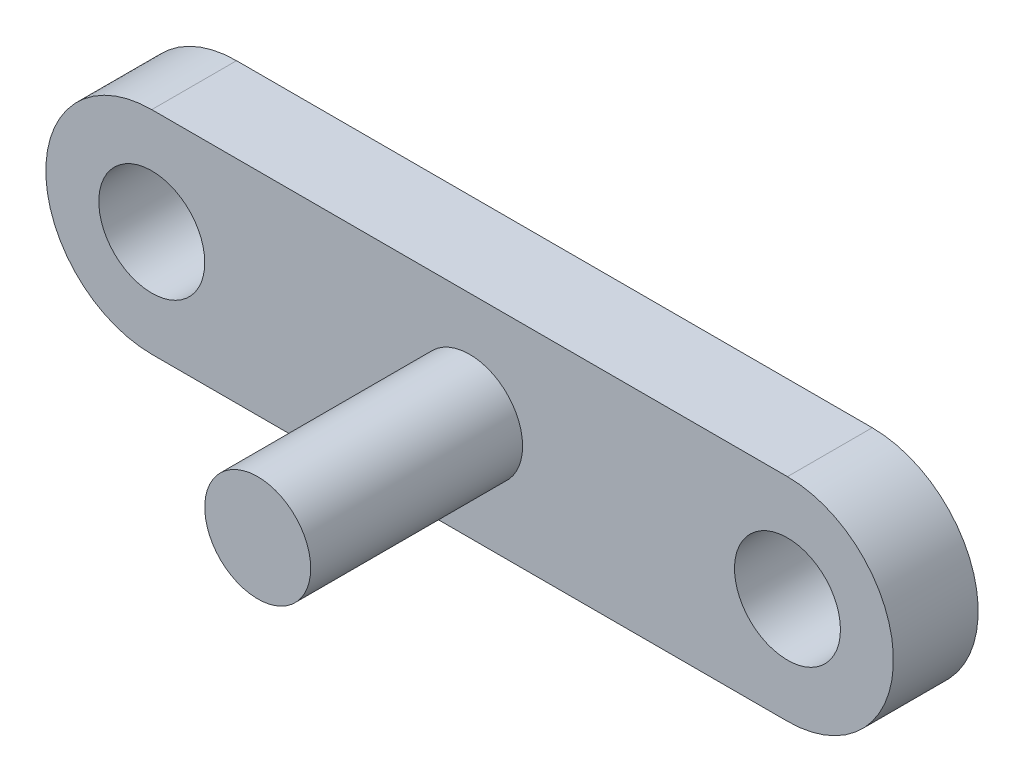
SolidWorks part; units mm, degrees
ref_plane "Front Plane" through (0, 0, 0) normal (0, 0, 1) x (1, 0, 0)
ref_plane "Top Plane" through (0, 0, 0) normal (0, 1, 0) x (1, 0, 0)
ref_plane "Right Plane" through (0, 0, 0) normal (1, 0, 0) x (0, 0, -1)
sketch "Sketch1" plane through (0, 0, 0) normal (0, 0, 1) x (1, 0, 0)
  line L1 (-57.7823, 15.6635) -> (-87.7823, 15.6635)
  line L3 (-57.7823, 5.6635) -> (-87.7823, 5.6635)
  arc A0 (-57.7823, 5.6635) -> (-57.7823, 15.6635) centre (-57.7823, 10.6635) ccw
  arc A1 (-87.7823, 15.6635) -> (-87.7823, 5.6635) centre (-87.7823, 10.6635) ccw
  circle A2 centre (-57.7823, 10.6635) radius 2.5
  circle A3 centre (-87.7823, 10.6635) radius 2.5
  dimension "D3" = 5
  dimension "D1" = 10
  dimension "D4" = 5
  dimension "D2" = 30
extrude "Boss-Extrude1" add sketch "Sketch1" along normal blind 4
sketch "Sketch2" plane through (0, 0, 4) normal (0, 0, 1) x (1, 0, 0)
  line L0 (-72.7823, 15.6635) -> (-72.7823, 5.6635) construction
  line L1 (-57.7823, 15.6635) -> (-87.7823, 15.6635) construction
  line L2 (-87.7823, 5.6635) -> (-57.7823, 5.6635) construction
  circle A0 centre (-72.7823, 10.6635) radius 2.5
  point P8 (-72.7823, 10.6635)
  dimension "D1" = 5
extrude "Boss-Extrude2" add sketch "Sketch2" along normal blind 10
